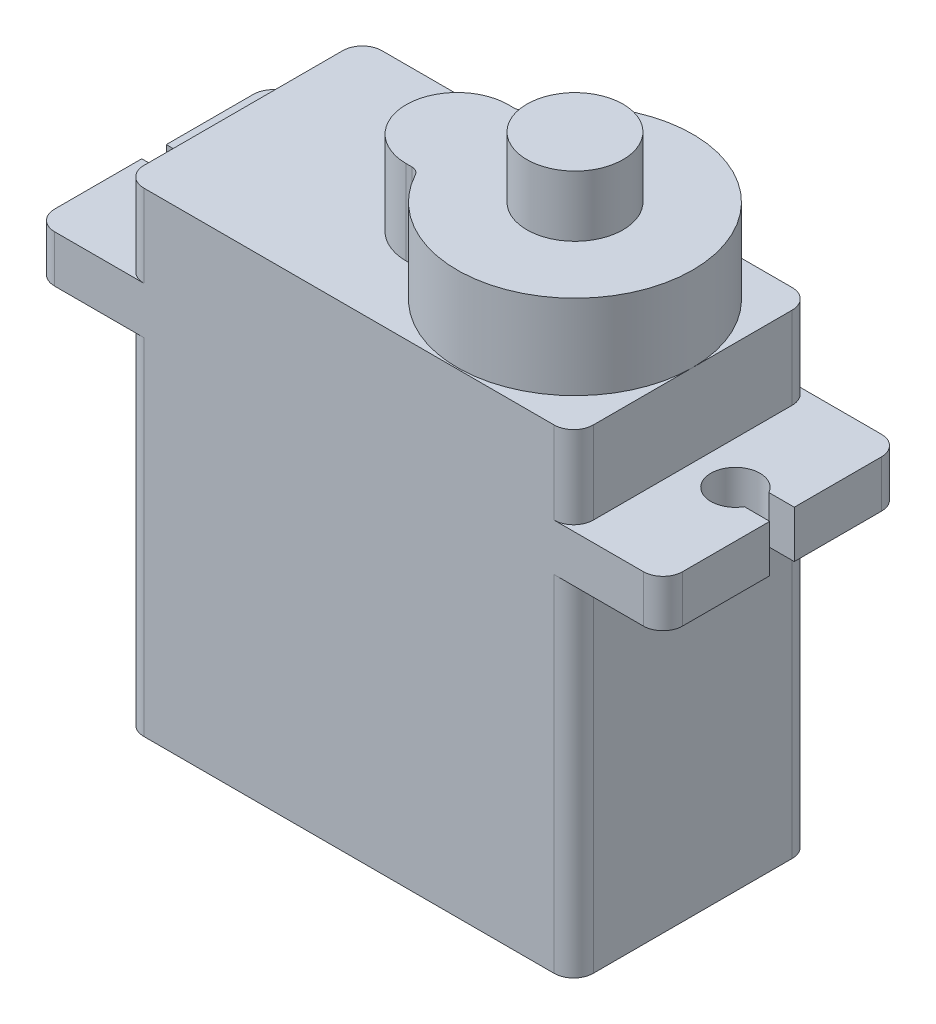
SolidWorks part; units mm, degrees
ref_plane "Plano frontal" through (0, 0, 0) normal (0, 0, 1) x (1, 0, 0)
ref_plane "Plano superior" through (0, 0, 0) normal (0, 1, 0) x (1, 0, 0)
ref_plane "Plano direito" through (0, 0, 0) normal (1, 0, 0) x (0, 0, -1)
sketch "Esboço2" plane through (0, 0, 0) normal (0, 1, 0) x (1, 0, 0)
  line L1 (11.45, 6.065) -> (-11.45, 6.065)
  line L2 (11.45, 6.065) -> (11.45, -6.065)
  line L3 (11.45, -6.065) -> (-11.45, -6.065)
  line L4 (-11.45, 6.065) -> (-11.45, -6.065)
  line L5 (11.45, 6.065) -> (-11.45, -6.065) construction
  line L6 (11.45, -6.065) -> (-11.45, 6.065) construction
  point P0 (0, 0)
  dimension "D1" = 22.9
  dimension "D2" = 12.13
extrude "Ressalto-extrusão1" add sketch "Esboço2" along normal blind 17.35
sketch "Esboço3" plane through (0, 17.35, 0) normal (0, 1, 0) x (1, 0, 0)
  line L1 (16, -6.065) -> (-16, -6.065)
  line L2 (16, -6.065) -> (16, 6.065)
  line L3 (16, 6.065) -> (-16, 6.065)
  line L4 (-16, -6.065) -> (-16, 6.065)
  line L5 (16, -6.065) -> (-16, 6.065) construction
  line L6 (16, 6.065) -> (-16, -6.065) construction
  line L7 (-11.45, -6.065) -> (11.45, -6.065) construction
  point P0 (0, 0)
  dimension "D1" = 32
  dimension "D2" = 0
extrude "Ressalto-extrusão2" add sketch "Esboço3" along normal blind 2.4
sketch "Esboço4" plane through (0, 19.75, 0) normal (0, 1, 0) x (1, 0, 0)
  line L1 (-11.45, -6.065) -> (11.45, -6.065)
  line L2 (-11.45, -6.065) -> (-11.45, 6.065)
  line L3 (-11.45, 6.065) -> (11.45, 6.065)
  line L4 (11.45, -6.065) -> (11.45, 6.065)
extrude "Ressalto-extrusão3" add sketch "Esboço4" along normal blind 4.45
sketch "Esboço5" plane through (0, 19.75, 0) normal (0, 1, 0) x (1, 0, 0)
  line L0 (0, -6.065) -> (0, 6.065) construction
  line L1 (-11.45, -6.065) -> (11.45, -6.065) construction
  line L2 (11.45, 6.065) -> (-11.45, 6.065) construction
  line L3 (-16, -0.625) -> (-16, 0.625)
  line L4 (-14.7075, 0.625) -> (-16, 0.625)
  line L5 (-14.7075, -0.625) -> (-16, -0.625)
  line L18 (14.7075, -0.625) -> (16, -0.625)
  line L19 (14.7075, 0.625) -> (16, 0.625)
  line L26 (16, -0.625) -> (16, 0.625)
  arc A0 (14.7075, 0.625) -> (14.7075, -0.625) centre (13.625, 0) ccw
  arc A1 (-14.7075, 0.625) -> (-14.7075, -0.625) centre (-13.625, 0) cw
  dimension "D2" = 2.5
extrude "Corte-extrusão1" cut sketch "Esboço5" against normal blind 2.4
sketch "Esboço6" plane through (0, 24.2, 0) normal (0, 1, 0) x (1, 0, 0)
  line L0 (11.25, -6) -> (11.25, 6) construction
  line L1 (-0.55, -2.6) -> (-0.2631, -2.6)
  line L3 (-0.55, 2.6) -> (-0.2631, 2.6)
  line L4 (11.45, -6.065) -> (11.45, 6.065) construction
  arc A0 (0.1763, -2.8615) -> (0.1763, 2.8615) centre (5.45, 0) ccw
  arc A1 (-0.55, 2.6) -> (-0.55, -2.6) centre (-0.55, 0) ccw
  arc A2 (0.1763, -2.8615) -> (-0.2631, -2.6) centre (-0.2631, -3.1) ccw
  arc A3 (0.1763, 2.8615) -> (-0.2631, 2.6) centre (-0.2631, 3.1) cw
  dimension "D2" = 0.5
  dimension "D1" = 12
  dimension "D3" = 6
extrude "Ressalto-extrusão4" add sketch "Esboço6" along normal blind 4.3
sketch "Esboço7" plane through (0, 28.5, 0) normal (0, 1, 0) x (1, 0, 0)
  circle A0 centre (5.45, 0) radius 2.45
  dimension "D1" = 4.9
extrude "Ressalto-extrusão5" add sketch "Esboço7" along normal blind 3.1
sketch "Esboço10" plane through (0, 28.5, 0) normal (0, 1, 0) x (1, 0, 0)
  line L1 (11.45, 6.065) -> (20.6404, 6.065)
  line L2 (11.45, 6.065) -> (11.45, -7.4178)
  line L3 (11.45, -7.4178) -> (20.6404, -7.4178)
  line L4 (20.6404, 6.065) -> (20.6404, -7.4178)
  line L5 (-11.45, 6.065) -> (-18.7442, 6.065)
  line L6 (-11.45, 6.065) -> (-11.45, -8.4924)
  line L7 (-11.45, -8.4924) -> (-18.7442, -8.4924)
  line L8 (-18.7442, 6.065) -> (-18.7442, -8.4924)
extrude "Corte-extrusão2" cut sketch "Esboço10" against normal blind 16 and the other way blind 1
ref_plane "Plano1" through (0, 17.6, 0) normal (0, 1, 0) x (1, 0, 0)
sketch "Esboço12" plane through (0, 17.6, 0) normal (0, 1, 0) x (1, 0, 0)
  line L1 (16, 0.625) -> (14.7075, 0.625)
  line L2 (16, 6.065) -> (11.45, 6.065)
  line L3 (16, 6.065) -> (16, 0.625)
  line L4 (16, -6.065) -> (11.45, -6.065)
  line L5 (11.45, 6.065) -> (11.45, -6.065)
  line L6 (16, -0.625) -> (14.7075, -0.625)
  line L7 (16, -0.625) -> (16, -6.065)
  line L8 (-16, -0.625) -> (-16, -6.065)
  line L9 (-16, -0.625) -> (-14.7075, -0.625)
  line L10 (-11.45, 6.065) -> (-11.45, -6.065)
  line L11 (-16, -6.065) -> (-11.45, -6.065)
  line L12 (-16, 6.065) -> (-16, 0.625)
  line L13 (-16, 6.065) -> (-11.45, 6.065)
  line L14 (-16, 0.625) -> (-14.7075, 0.625)
  arc A0 (14.7075, 0.625) -> (14.7075, -0.625) centre (13.625, 0) ccw
  arc A1 (-14.7075, 0.625) -> (-14.7075, -0.625) centre (-13.625, 0) cw
extrude "Ressalto-extrusão7" add sketch "Esboço12" along normal blind 2.4
fillet "Filete1" radius 1 12 edges at (-16, 18.8, -6.065) (-16, 18.8, 6.065) (16, 18.8, -6.065) (16, 18.8, 6.065) (-11.45, 8.8, 6.065) (-11.45, 22.1, 6.065) (11.45, 22.1, 6.065) (11.45, 8.8, 6.065) (-11.45, 8.8, -6.065) (-11.45, 22.1, -6.065) (11.45, 8.8, -6.065) (11.45, 22.1, -6.065)
